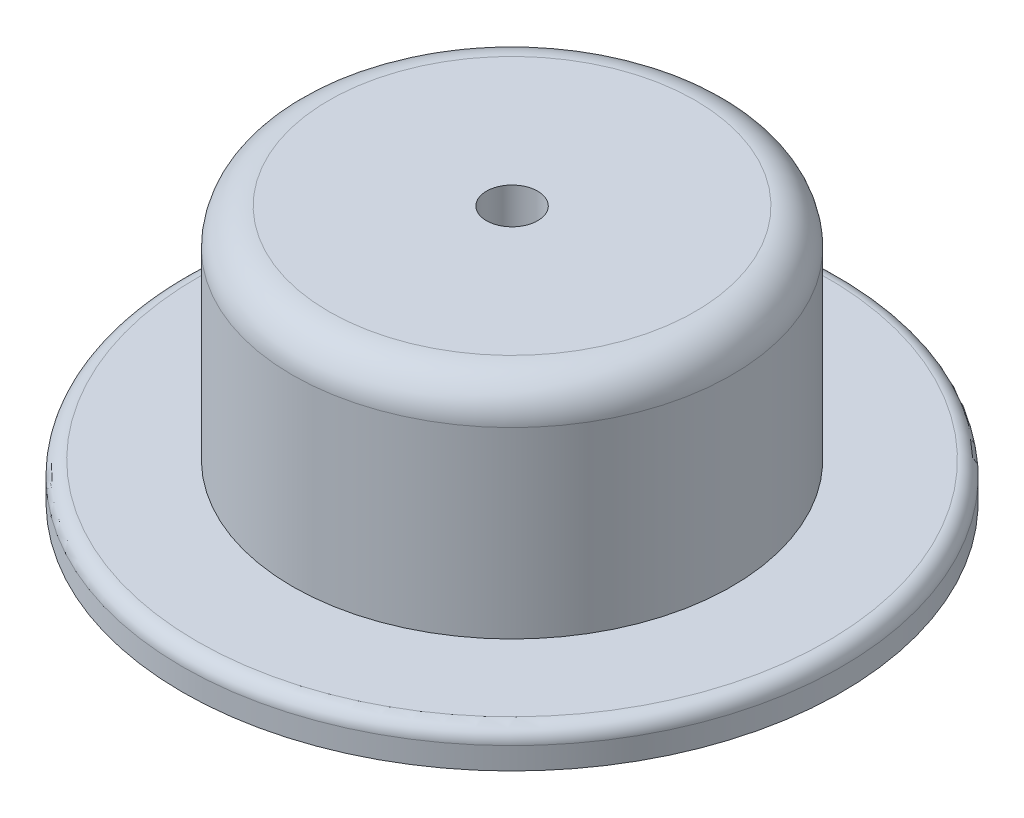
SolidWorks part; units mm, degrees
ref_plane "Front Plane" through (0, 0, 0) normal (0, 0, 1) x (1, 0, 0)
ref_plane "Top Plane" through (0, 0, 0) normal (0, 1, 0) x (1, 0, 0)
ref_plane "Right Plane" through (0, 0, 0) normal (1, 0, 0) x (0, 0, -1)
sketch "Sketch1" plane through (0, 0, 0) normal (0, 1, 0) x (1, 0, 0)
  circle A0 centre (0, 0) radius 4.5
  circle A1 centre (0, 0) radius 0.375
  dimension "D1" = 9
  dimension "D2" = 0.75
extrude "Boss-Extrude1" add sketch "Sketch1" along normal blind 0.5
sketch "Sketch2" plane through (0, 0.5, 0) normal (0, 1, 0) x (1, 0, 0)
  circle A0 centre (0, 0) radius 3
  circle A2 centre (0, 0) radius 0.35
  dimension "6" = 6
  dimension "D2" = 0.7
extrude "Boss-Extrude2" add sketch "Sketch2" along normal blind 3
fillet "Fillet1" radius 0.5 1 edges at (0, 3.5, 3)
fillet "Fillet2" radius 0.2 1 edges at (0, 0.5, 4.5)
